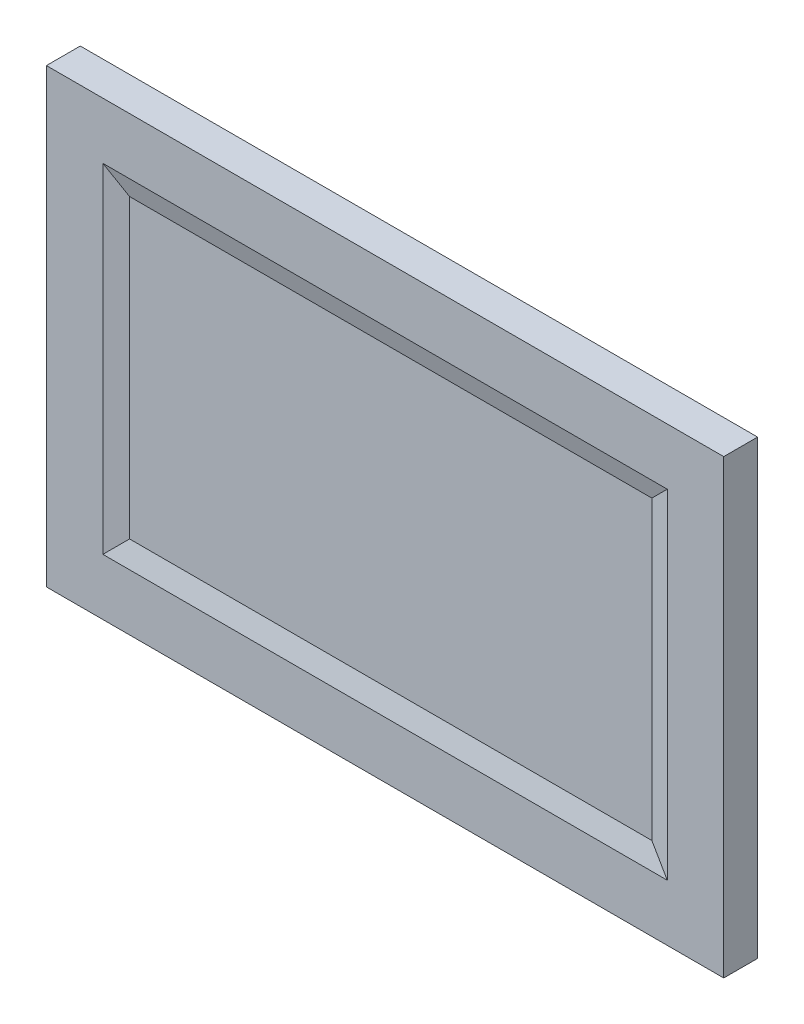
SolidWorks part; units mm, degrees
ref_plane "Front Plane" through (0, 0, 0) normal (0, 0, 1) x (1, 0, 0)
ref_plane "Top Plane" through (0, 0, 0) normal (0, 1, 0) x (1, 0, 0)
ref_plane "Right Plane" through (0, 0, 0) normal (1, 0, 0) x (0, 0, -1)
sketch "Sketch2" plane through (0, 0, 0) normal (0, 0, 1) x (1, 0, 0)
  line L1 (60, -40) -> (-60, -40)
  line L2 (60, -40) -> (60, 40)
  line L3 (60, 40) -> (-60, 40)
  line L4 (-60, -40) -> (-60, 40)
  line L5 (60, -40) -> (-60, 40) construction
  line L6 (60, 40) -> (-60, -40) construction
  point P0 (0, 0)
  dimension "D1" = 80
  dimension "D2" = 120
extrude "Boss-Extrude1" add sketch "Sketch2" along normal mid plane 6
sketch "Sketch3" plane through (0, 0, 3) normal (0, 0, 1) x (1, 0, 0)
  line L8 (-50, 30) -> (-50, -30)
  line L9 (-50, -30) -> (50, -30)
  line L10 (50, -30) -> (50, 30)
  line L11 (50, 30) -> (-50, 30)
  line L12 (-50, 30) -> (-50, -30)
  line L13 (-50, -30) -> (50, -30)
  line L14 (50, -30) -> (50, 30)
  line L15 (50, 30) -> (-50, 30)
  dimension "D1" = 10
extrude "Cut-Extrude1" cut sketch "Sketch3" against normal mid plane 2 draft 75
mirror "Mirror1" about plane through (0, 0, 0) normal (0, 0, 1) of "Cut-Extrude1"
sketch "Sketch4" plane through (0, 0, -2) normal (0, 0, -1) x (-1, 0, 0)
  line L0 (-41.4522, -22.0177) -> (-12.0544, -22.0177) construction
  text T0 "No homo"
  point P3 (0, 0)
extrude "Boss-Extrude2" add sketch "Sketch4" along normal mid plane 0.5
